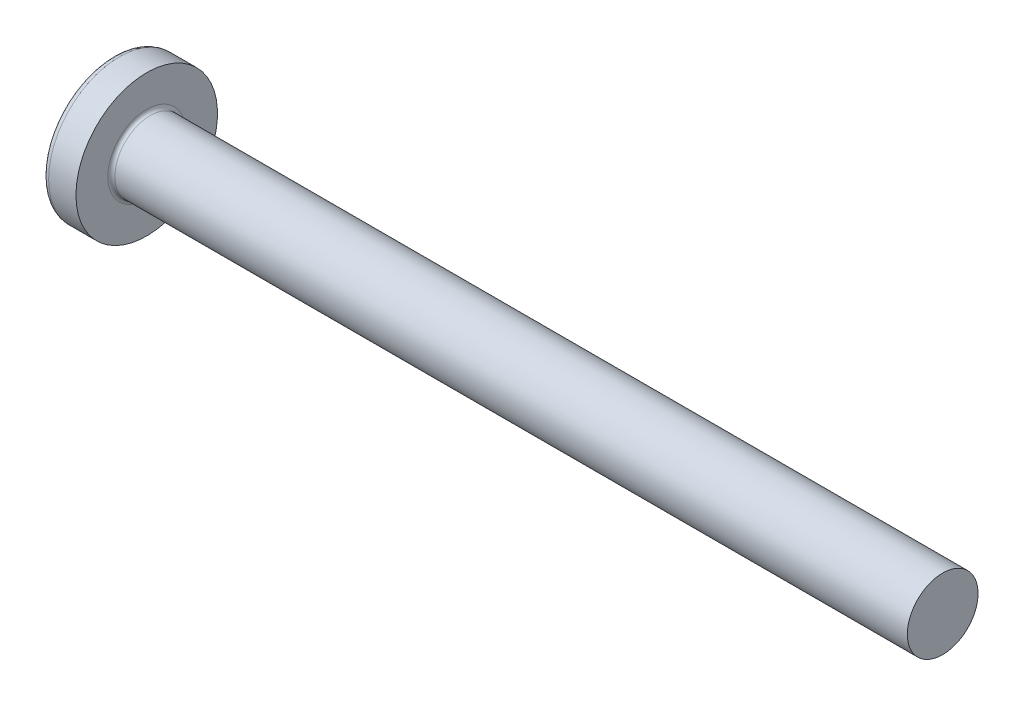
SolidWorks part; units mm, degrees
ref_plane "Plane1" through (0, 0, 0) normal (0, 0, 1) x (1, 0, 0)
ref_plane "Plane2" through (0, 0, 0) normal (0, 1, 0) x (1, 0, 0)
ref_plane "Plane3" through (0, 0, 0) normal (1, 0, 0) x (0, 0, -1)
sketch "BodySke" plane through (0, 0, 0) normal (0, 0, 1) x (1, 0, 0)
  line L0 (3.1, 2) -> (3.1, 4)
  line L1 (3.45, 6.35) -> (3.45, -3.175) construction
  line L2 (-25.4, 0) -> (127, 0) construction
  line L3 (48.1, 0) -> (0, 0)
  line L4 (3.1, 2) -> (48.1, 2)
  line L5 (48.1, 2) -> (48.1, 0)
  line L6 (1.5553, 4) -> (3.1, 4)
  line L8 (3.1, 6.35) -> (3.1, -3.175) construction
  arc A0 (1.2654, 3.8534) -> (0, 0) centre (6.5, 0) ccw
  arc A2 (1.2654, 3.8534) -> (1.5553, 4) centre (1.5553, 3.64) cw
  dimension "Head_crown_rad" = 6.5
  dimension "Head_fillet_rad" = 0.36
  dimension "Length" = 45
  dimension "Head_ht" = 3.1
  dimension "Head_dia" = 8
  dimension "Advance" = 0.7
  dimension "Thread_nom" = 45
  dimension "Diameter" = 4
revolve "Base-Revolve" add sketch "BodySke"
cosmetic thread "ThreadCosmetic" [suppressed]
fillet "Fillet1" radius 0.2 1 edges at (3.1, 0, 2)
sketch "Sketch3" plane through (0, 0, 0) normal (1, 0, 0) x (0, 0, -1)
  line L0 (0.515, -2.15) -> (-0.515, -2.15)
  line L1 (0.515, -2.15) -> (0.515, 2.15)
  line L2 (-0.515, 2.15) -> (0.515, 2.15)
  line L3 (-0.515, 2.15) -> (-0.515, -2.15)
  dimension "Cross_dia" = 4.3
  dimension "D1" = 2.15
  dimension "Cross_width" = 1.03
  dimension "D2" = 0.515
ref_plane "Plane4" through (2.34, 0, 0) normal (1, 0, 0) x (0, 0, -1)
sketch "Sketch4" plane through (2.34, 0, 0) normal (1, 0, 0) x (0, 0, -1)
  line L0 (0.515, -0.9833) -> (-0.515, -0.9833)
  line L1 (0.515, -0.9833) -> (0.515, 0.9833)
  line L2 (-0.515, 0.9833) -> (0.515, 0.9833)
  line L3 (-0.515, 0.9833) -> (-0.515, -0.9833)
  dimension "D1" = 1.03
  dimension "D2" = 1.9666
  dimension "D3" = 0.515
  dimension "D4" = 0.9833
loft "Recess" cut profiles "Sketch3", "Sketch4"
pattern_circular "RecPat" count 2 every 90 about axis through (0, 0, 0) along (1, 0, 0) of "Recess"
sketch "RecCorSke" plane through (0, 0, 0) normal (0, 0, 1) x (1, 0, 0)
  line L0 (-3.175, 0) -> (15.875, 0) construction
  line L1 (-25.4, 0) -> (127, 0) construction
  line L2 (0, 0) -> (0, 1.0146)
  line L3 (0, 1.0146) -> (2.34, 0.851)
  line L4 (2.34, 0.851) -> (2.6165, 0)
  line L5 (2.6165, 0) -> (0, 0)
  dimension "Diameter" = 1.702
  dimension "Depth" = 2.34
  dimension "Draft_angle" = 4
  dimension "Bottom_angle" = 18
revolve "RecessCore" cut sketch "RecCorSke" angle 360 about L0
sketch "ThdSchSke" plane through (0, 0, 0) normal (0, 0, 1) x (1, 0, 0)
  line L0 (4.5, -1.61) -> (4.2269, -2)
  line L1 (4.5, -1.61) -> (4.7731, -2)
  line L2 (4.7731, -2) -> (4.7731, -2.5)
  line L3 (-3.175, 0) -> (5.1513, 0) construction
  line L5 (4.7731, -2.5) -> (4.2269, -2.5)
  line L6 (4.2269, -2.5) -> (4.2269, -2)
  dimension "Diameter" = 4
  dimension "SideAngle" = 55
  dimension "VeeAngle" = 70
  dimension "Thread_minor" = 3.22
  dimension "Overcut" = 5
  dimension "Start" = 4.5
revolve "ThreadSchematic" [suppressed] cut sketch "ThdSchSke" angle 360 about L3
pattern_linear "ThdSchPat" [suppressed]
equation "\"D1@Sketch3\" = \"Cross_dia@Sketch3\" / 2"
equation "\"D2@Sketch3\" = \"Cross_width@Sketch3\" / 2"
equation "\"Depth@RecCorSke\" = \"Cross_depth@Plane4\""
equation "\"D1@Sketch4\" = \"Cross_width@Sketch3\""
equation "\"D2@Sketch4\" = \"Cross_dia@Sketch3\" - 2.0 * \"Cross_depth@Plane4\" * tan(26.5  * 0.017453292)"
equation "\"D3@Sketch4\" = \"D1@Sketch4\" / 2"
equation "\"D4@Sketch4\" = \"D2@Sketch4\" / 2"
equation "\"Thread_length@ThreadCosmetic\" = ((sgn( (\"Length@BodySke\" - \"Advance@BodySke\" * 2.0 ) - \"Thread_nom@BodySke\" )-1)*( (\"Length@BodySke\" - \"Advance@BodySke\" * 2.0 ) - \"Thread_nom@BodySke\" ))/-2+ \"Thread_nom@BodySke\""
equation "\"Thread_minor@ThdSchSke\" = \"Thread_minor@ThreadCosmetic\""
equation "\"Diameter@ThdSchSke\" = \"Diameter@BodySke\""
equation "\"Overcut@ThdSchSke\" = \"Diameter@BodySke\" * 1.25"
equation "\"Start@ThdSchSke\" = \"Head_ht@BodySke\" + \"Length@BodySke\" - \"Thread_length@ThreadCosmetic\"  '---Non-countersunk---"
equation "\"Num_threads@ThdSchPat\" = int( \"Thread_length@ThreadCosmetic\" / \"Advance@BodySke\" + 0.999 )  + 1"
equation "\"Advance@ThdSchPat\" = \"Thread_length@ThreadCosmetic\" /  (\"Num_threads@ThdSchPat\" - 1) 'relax it"
